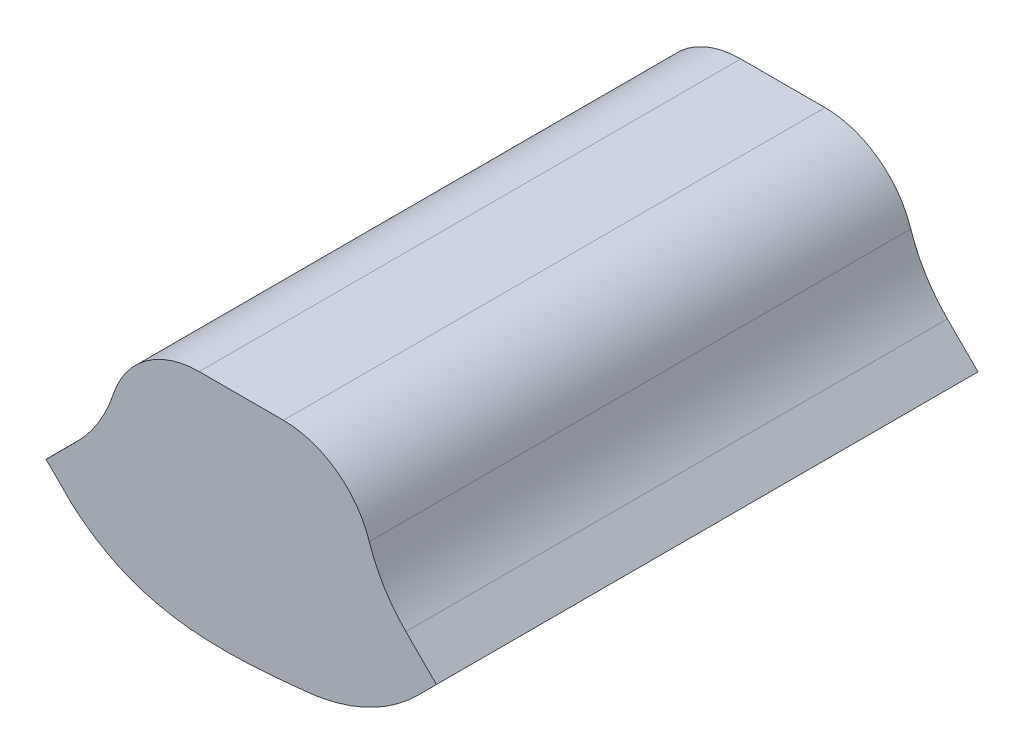
SolidWorks part; units mm, degrees
ref_plane "Front Plane" through (0, 0, 0) normal (0, 0, 1) x (1, 0, 0)
ref_plane "Top Plane" through (0, 0, 0) normal (0, 1, 0) x (1, 0, 0)
ref_plane "Right Plane" through (0, 0, 0) normal (1, 0, 0) x (0, 0, -1)
sketch "Sketch1" plane through (0, 0, 0) normal (0, 0, 1) x (1, 0, 0)
  line L0 (-7.1631, -7.2936) -> (-4.4267, -4.5573) construction
  line L1 (-19.5248, -6.6807) -> (-18.6705, -7.5349) construction
  line L2 (-18.5006, -5.6614) -> (-19.4516, -6.6123) construction
  line L3 (-6.6123, -6.6123) -> (-7.5633, -5.6614) construction
  line L4 (-14.4324, -1.6123) -> (-11.6315, -1.6123) construction
  line L5 (-7.1631, -7.2936) -> (-6.5471, -6.6776)
  line L6 (-19.5248, -6.6807) -> (-18.6705, -7.5349)
  line L7 (-18.5006, -5.6614) -> (-19.4516, -6.6123)
  line L8 (-6.6123, -6.6123) -> (-7.5633, -5.6614)
  line L9 (-14.4324, -1.6123) -> (-11.6315, -1.6123)
  line L10 (-19.4516, -6.6123) -> (-19.5248, -6.6807)
  line L11 (-6.6123, -6.6123) -> (-6.5471, -6.6776)
  arc A0 (-8.7801, -3.6799) -> (-7.5633, -5.6614) centre (-4.0278, -2.1258) ccw construction
  arc A1 (-8.7801, -3.6799) -> (-11.6315, -1.6123) centre (-11.6315, -4.6123) ccw construction
  arc A2 (-14.4324, -1.6123) -> (-17.2838, -3.6799) centre (-14.4324, -4.6123) ccw construction
  arc A3 (-18.5006, -5.6614) -> (-17.2838, -3.6799) centre (-22.0362, -2.1258) ccw construction
  arc A4 (-8.7801, -3.6799) -> (-7.5633, -5.6614) centre (-4.0278, -2.1258) ccw
  arc A5 (-8.7801, -3.6799) -> (-11.6315, -1.6123) centre (-11.6315, -4.6123) ccw
  arc A6 (-14.4324, -1.6123) -> (-17.2838, -3.6799) centre (-14.4324, -4.6123) ccw
  arc A7 (-18.5006, -5.6614) -> (-17.2838, -3.6799) centre (-22.0362, -2.1258) ccw
  spline S0 degree 2 poles (-545.3495, 835.5315) (37.021, 23.8755) (-7.9481, -7.956) (-8.3694, -8.2542) (-8.8334, -8.4765) (-9.296, -8.6982) (-9.7921, -8.8395) (-62.5131, -23.8571) (-332.4777, 937.8112) knots -26.527281 -26.527281 -26.527281 0.25 0.25 0.5 0.5 0.75 0.75 27.553277 27.553277 27.553277 only from (-7.1631, -7.2936) to (-10.7945, -9.0346) construction
  spline S1 degree 3 poles (-94.4411, 989.5891) (-37.0446, 79.0727) (-32.7923, -3.1834) (-16.0665, -8.9581) (-14.8062, -9.2005) (-13.1209, -9.2553) (7.1067, -7.4846) (27.1312, 3.6385) (34.9979, -1007.977) knots -6.173189 -6.173189 -6.173189 -6.173189 0.231048 0.351383 0.481746 0.716878 0.971604 7.69899 7.69899 7.69899 7.69899 weights 1 1 1 1 1 1 1 1 1 only from (-18.6705, -7.5349) to (-10.7945, -9.0346) construction
  spline S2 degree 2 poles (-7.1631, -7.2936) (-7.5283, -7.6588) (-7.9481, -7.956) (-8.3694, -8.2542) (-8.8334, -8.4765) (-9.296, -8.6982) (-9.7921, -8.8395) (-10.2838, -8.9795) (-10.7945, -9.0346) knots 0 0 0 0.25 0.25 0.5 0.5 0.75 0.75 1 1 1
  spline S3 degree 3 poles (-18.6705, -7.5349) (-18.1251, -8.013) (-17.2772, -8.54) (-16.0665, -8.9581) (-14.8062, -9.2005) (-13.1209, -9.2553) (-11.6684, -9.1282) (-10.8741, -9.0432) (-10.7945, -9.0346) knots 0 0 0 0 0.231048 0.351383 0.481746 0.716878 0.971604 1 1 1 1 weights 1 1 1 1 1 1 1 1 1
extrude "Boss-Extrude1" add sketch "Sketch1" against normal up to surface (18 mm away)
